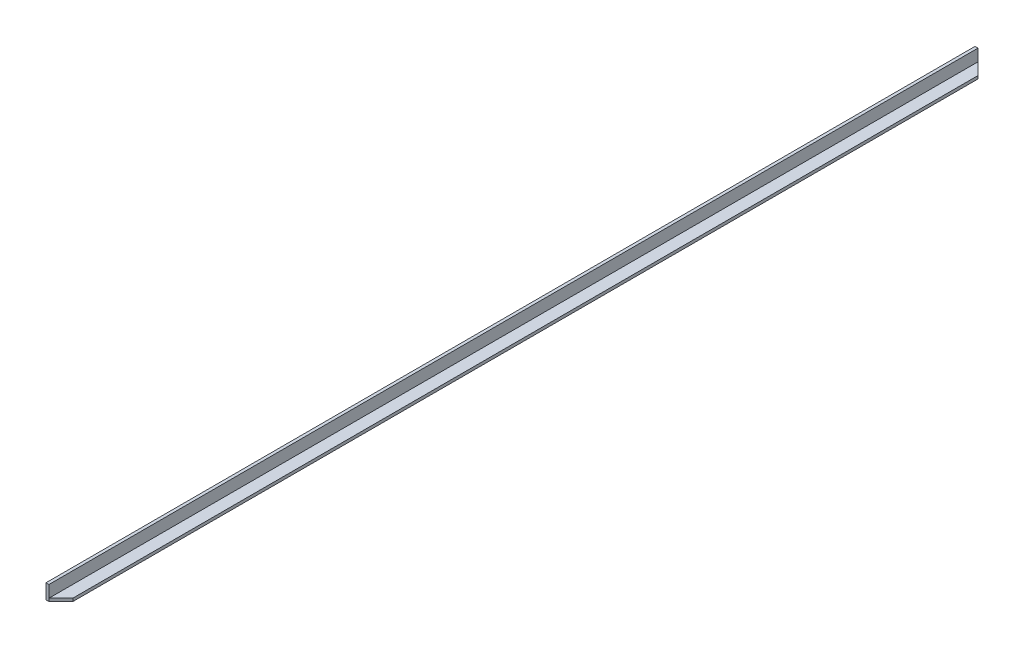
SolidWorks part; units mm, degrees
ref_plane "Front" through (0, 0, 0) normal (0, 0, 1) x (1, 0, 0)
ref_plane "Top" through (0, 0, 0) normal (0, 1, 0) x (1, 0, 0)
ref_plane "Right" through (0, 0, 0) normal (1, 0, 0) x (0, 0, -1)
sketch "Эскиз1" plane through (0, 0, 0) normal (0, 0, 1) x (1, 0, 0)
  line L0 (-10, 0) -> (10, 0)
  line L1 (-10, 0) -> (-10, 20)
  line L2 (-10, 20) -> (-6, 20)
  line L3 (-6, 20) -> (-6, 4)
  line L4 (-6, 4) -> (10, 4)
  line L5 (10, 4) -> (10, 0)
  dimension "D1" = 20
  dimension "D2" = 4
extrude "Бобышка-Вытянуть1" add sketch "Эскиз1" along normal blind 1250
sketch "Эскиз2" plane through (0, 4, 0) normal (0, 1, 0) x (1, 0, 0)
  line L0 (-6, 0) -> (10, -16)
  line L1 (10, -1250) -> (10, 0) construction
  line L2 (10, -16) -> (10, 0)
  line L3 (10, 0) -> (-6, 0)
extrude "Вырез-Вытянуть1" cut sketch "Эскиз2" against normal through all
sketch "Эскиз3" plane through (0, 4, 0) normal (0, 1, 0) x (1, 0, 0)
  line L0 (-6, -1250) -> (10, -1234)
  line L1 (10, -1250) -> (10, -16) construction
  line L2 (10, -1234) -> (10, -1250)
  line L3 (10, -1250) -> (-6, -1250)
extrude "Вырез-Вытянуть2" cut sketch "Эскиз3" against normal through all
